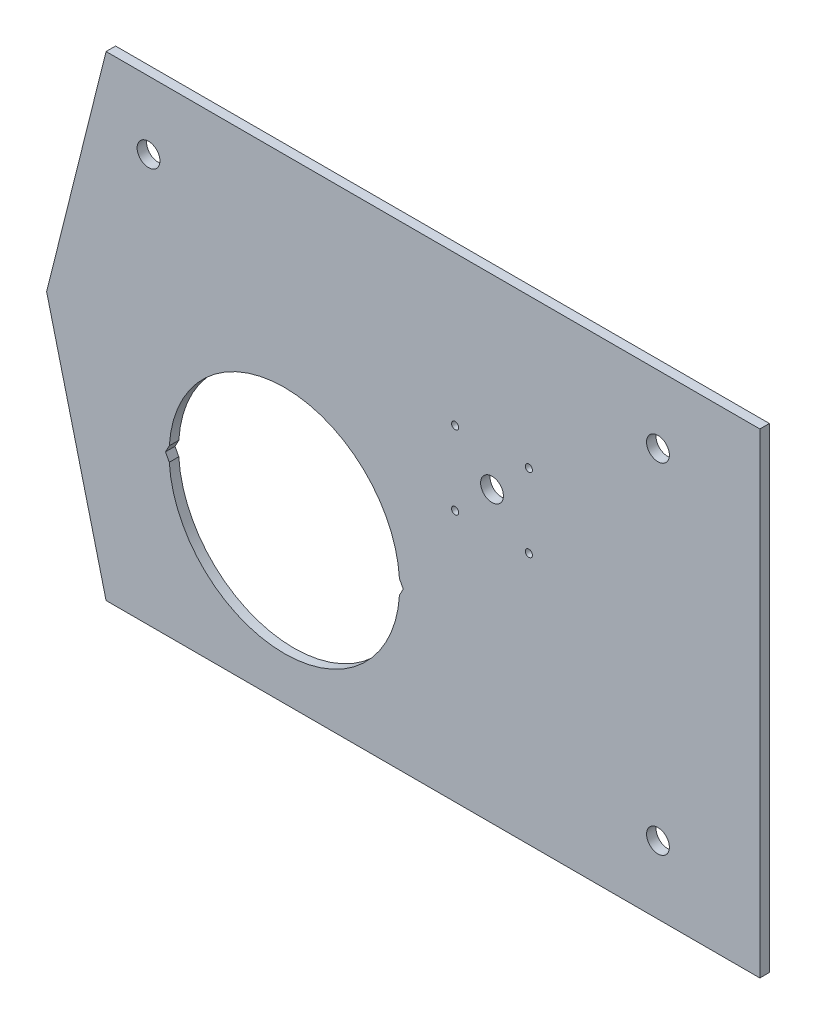
SolidWorks part; units mm, degrees
ref_plane "Front Plane" through (0, 0, 0) normal (0, 0, 1) x (1, 0, 0)
ref_plane "Top Plane" through (0, 0, 0) normal (0, 1, 0) x (1, 0, 0)
ref_plane "Right Plane" through (0, 0, 0) normal (1, 0, 0) x (0, 0, -1)
sketch "Sketch1" plane through (0, 0, 0) normal (0, 0, 1) x (1, 0, 0)
  line L0 (-50, 100) -> (-50, -100) construction
  line L1 (150, -100) -> (-150, -100)
  line L2 (150, -100) -> (150, 100)
  line L3 (150, 100) -> (-150, 100)
  line L4 (-150, -100) -> (-150, 100)
  line L5 (150, -100) -> (-150, 100) construction
  line L6 (150, 100) -> (-150, -100) construction
  line L7 (107.1429, 71.4286) -> (107.1429, -76.2286) construction
  line L8 (-150, 0) -> (150, 0) construction
  line L9 (-107.1429, 71.4286) -> (107.1429, 71.4286) construction
  line L10 (58.4824, 0.502) -> (16.1824, 0.502) construction
  line L11 (58.4824, 0.502) -> (58.4824, 42.802) construction
  line L12 (58.4824, 42.802) -> (16.1824, 42.802) construction
  line L13 (16.1824, 0.502) -> (16.1824, 42.802) construction
  line L14 (58.4824, 0.502) -> (16.1824, 42.802) construction
  line L15 (58.4824, 42.802) -> (16.1824, 0.502) construction
  line L16 (52.8324, 6.152) -> (21.8324, 6.152) construction
  line L17 (52.8324, 6.152) -> (52.8324, 37.152) construction
  line L18 (52.8324, 37.152) -> (21.8324, 37.152) construction
  line L19 (21.8324, 6.152) -> (21.8324, 37.152) construction
  line L20 (52.8324, 6.152) -> (21.8324, 37.152) construction
  line L21 (52.8324, 37.152) -> (21.8324, 6.152) construction
  line L22 (0, 71.4286) -> (107.1429, -71.4286) construction
  line L23 (-107.1429, 71.4286) -> (107.1429, -2.4) construction
  line L24 (-125, 100) -> (-125, -100) construction
  line L25 (-125, -100) -> (-150, 0)
  line L26 (-150, 0) -> (-125, 100)
  line L27 (-98.5, -33.3333) -> (0, -33.3333) construction
  line L28 (-98.4071, -30.3333) -> (-1.5929, -30.3333) construction
  line L29 (-1.5929, -36.3333) -> (-98.4071, -36.3333) construction
  line L30 (-1.5929, -36.3333) -> (0, -33.3333)
  line L31 (0, -33.3333) -> (-1.5929, -30.3333)
  line L32 (-98.4071, -36.3333) -> (-100, -33.3333)
  line L33 (-100, -33.3333) -> (-98.4071, -30.3333)
  circle A0 centre (21.8324, 37.152) radius 1.5
  circle A1 centre (52.8324, 37.152) radius 1.5
  circle A2 centre (52.8324, 6.152) radius 1.5
  circle A3 centre (21.8324, 6.152) radius 1.5
  circle A4 centre (107.1429, 71.4286) radius 4.8
  circle A5 centre (107.1429, -71.4286) radius 4.8
  circle A6 centre (37.3324, 21.652) radius 4.8
  arc A7 (-1.5929, -30.3333) -> (-98.4071, -30.3333) centre (-50, -33.3333) ccw
  circle A8 centre (-107.1429, 71.4286) radius 4.8
  circle A9 centre (-50, -33.3333) radius 48.5 construction
  circle A10 centre (-50, -33.3333) radius 50 construction
  arc A11 (-98.4071, -36.3333) -> (-1.5929, -36.3333) centre (-50, -33.3333) ccw
  point P0 (0, 0)
  point P6 (-107.1429, 71.4286)
  point P7 (107.1429, 71.4286)
  point P12 (37.3324, 21.652)
  point P27 (107.1429, 71.4286)
  point P28 (107.1429, -71.4286)
  point P36 (-50, -33.3333)
  point P43 (37.3324, 21.652)
  dimension "D5" = 3
  dimension "D6" = 3
  dimension "D7" = 3
  dimension "D8" = 3
  dimension "D13" = 9.6
  dimension "D14" = 9.6
  dimension "D15" = 9.6
  dimension "D17" = 9.6
  dimension "D19" = 97
  dimension "D20" = 100
  dimension "D1" = 300
  dimension "D2" = 200
  dimension "D3" = 42.3
  dimension "D4" = 42.3
  dimension "D9" = 31
  dimension "D10" = 31
  dimension "D11" = 42.8571
  dimension "D12" = 100
  dimension "D18" = 25
  dimension "D21" = 3
  dimension "D22" = 3
sketch "Sketch2" plane through (0, 0, 0) normal (0, 0, 1) x (1, 0, 0)
  line L1 (-108.014, -138.1365) -> (191.986, -138.1365)
  line L2 (-108.014, -138.1365) -> (-108.014, -142.1365)
  line L3 (-108.014, -142.1365) -> (191.986, -142.1365)
  line L4 (191.986, -138.1365) -> (191.986, -142.1365)
  line L5 (41.986, -142.1365) -> (41.986, -138.1365) construction
  line L6 (-108.014, -140.1365) -> (191.986, -140.1365) construction
  point P152 (41.986, -140.1365)
  dimension "D1" = 300
  dimension "D2" = 4
extrude "Boss-Extrude3" add sketch "Sketch1" along normal blind 4
equation "\"H\"= 200"
equation "\"L\" = 300"
equation "\"nema_internal\"= 31"
equation "\"nema_external\"= 42.3"
equation "\"bars\"= 9.60"
equation "\"trehead_rods\"= 8"
equation "\"hole_nema\"= 3"
equation "\"D1@Sketch1\"=\"L\""
equation "\"D2@Sketch1\"=\"H\""
equation "\"D3@Sketch1\"=\"nema_external\""
equation "\"D4@Sketch1\"=\"nema_external\""
equation "\"D5@Sketch1\"=\"hole_nema\""
equation "\"D6@Sketch1\"=\"hole_nema\""
equation "\"D7@Sketch1\"=\"hole_nema\""
equation "\"D8@Sketch1\"=\"hole_nema\""
equation "\"D9@Sketch1\"=\"nema_internal\""
equation "\"D10@Sketch1\"=\"nema_internal\""
equation "\"D11@Sketch1\"=\"L\"/7"
equation "\"D12@Sketch1\"=\"L\"/3"
equation "\"D13@Sketch1\"=\"bars\""
equation "\"D14@Sketch1\"=\"bars\""
equation "\"D15@Sketch1\"=\"bars\""
equation "\"ring_dimension_max\" = 80"
equation "\"thik_material\"= 4"
equation "\"D17@Sketch1\"=\"bars\""
equation "\"D18@Sketch1\"=\"L\"/12"
equation "\"D1@Sketch2\"=\"L\""
equation "\"D2@Sketch2\"=\"thik_material\""
equation "\"kerf\"= 1"
equation "\"D1@Boss-Extrude3\"=\"thik_material\""
equation "\"ring_b\"=100"
equation "\"D19@Sketch1\"=\"ring_b\"-3"
equation "\"D20@Sketch1\"=\"ring_b\""
